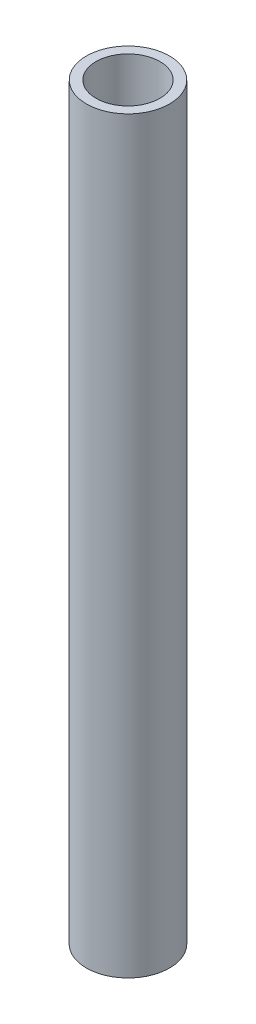
SolidWorks part; units mm, degrees
material "AISI 4130 Steel, annealed at 865C"
ref_plane "X-Y Datum" through (0, 0, 0) normal (0, 0, 1) x (1, 0, 0)
ref_plane "X-Z Datum" through (0, 0, 0) normal (0, 1, 0) x (1, 0, 0)
ref_plane "Y-Z Datum" through (0, 0, 0) normal (1, 0, 0) x (0, 0, -1)
sketch "Sketch1" plane through (0, 0, 0) normal (0, 1, 0) x (1, 0, 0)
  circle A0 centre (0, 0) radius 6.35
  circle A1 centre (0, 0) radius 4.8768
  dimension "D1" = 12.7
  dimension "D2" = 1.4732
extrude "Boss-Extrude1" add sketch "Sketch1" along normal blind 114.3
equation "\"Push rod tube length\"= 4.5in"
equation "\"D1@Boss-Extrude1\"=\"Push rod tube length\""
